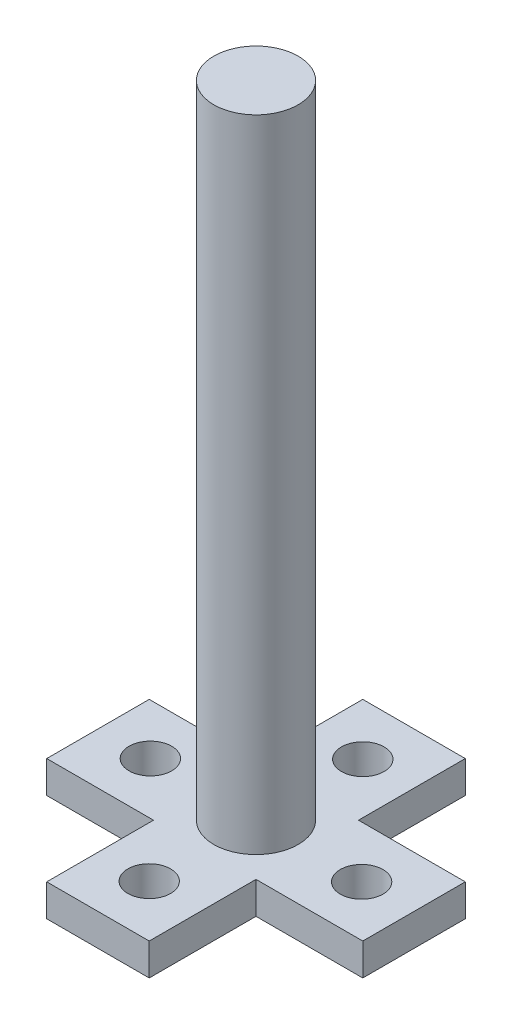
SolidWorks part; units mm, degrees
ref_plane "前视基准面" through (0, 0, 0) normal (0, 0, 1) x (1, 0, 0)
ref_plane "上视基准面" through (0, 0, 0) normal (0, 1, 0) x (1, 0, 0)
ref_plane "右视基准面" through (0, 0, 0) normal (1, 0, 0) x (0, 0, -1)
other "Configuration Table"
sketch "草图1" plane through (0, 0, 0) normal (0, 1, 0) x (1, 0, 0)
  line L0 (-14.9378, 4.9391) -> (35717.0744, -34969.6704) construction
  line L5 (-15, -5) -> (15, 5) construction
  line L6 (-15, 5) -> (15, -5) construction
  line L11 (-5, -15) -> (5, 15) construction
  line L12 (-5, 15) -> (5, -15) construction
  line L13 (-5, 5) -> (-35360.3391, -35350.3391) construction
  line L14 (5, 5) -> (35360.3391, -35350.3391) construction
  line L15 (5, -5) -> (-35350.3391, -35360.3391) construction
  line L16 (-4.8, 14.8) -> (4.8, 14.8)
  line L17 (4.8, -14.8) -> (4.8, 14.8)
  line L18 (-4.8, -14.8) -> (4.8, -14.8)
  line L19 (-4.8, -14.8) -> (-4.8, 14.8)
  line L20 (-14.8, 4.8) -> (14.8, 4.8)
  line L21 (14.8, -4.8) -> (14.8, 4.8)
  line L22 (-14.8, -4.8) -> (14.8, -4.8)
  line L23 (-14.8, -4.8) -> (-14.8, 4.8)
  circle A0 centre (0, 0) radius 4
  circle A1 centre (-9.9464, 0.0536) radius 2
  circle A2 centre (0.0536, 9.9464) radius 2
  circle A3 centre (9.9464, -0.0536) radius 2
  circle A4 centre (-0.0536, -9.9464) radius 2
  point P0 (0, 0)
  point P6 (0, 0)
  dimension "D5" = 8
  dimension "D6" = 4
  dimension "D1" = 30
  dimension "D2" = 30
  dimension "D3" = 10
  dimension "D4" = 10
  dimension "D7" = 4
extrude "凸台-拉伸2" add sketch "草图1" along normal blind 3 contours L23 L22 L19 L20 A1 | L22 L19 L18 L17 A4 | L19 L22 L17 L20 A0 | L17 L22 L21 L20 A3 | L19 L20 L17 L16 A2 | A0
sketch "草图2" plane through (0, 3, 0) normal (0, 1, 0) x (1, 0, 0)
  circle A0 centre (0, 0) radius 3.95
  dimension "D1" = 7.9
extrude "凸台-拉伸3" add sketch "草图2" along normal blind 120
sketch "草图3" plane through (0, 123, 0) normal (0, 1, 0) x (1, 0, 0)
  circle A0 centre (0, 0) radius 3.95
extrude "切除-拉伸1" cut sketch "草图3" against normal blind 60
